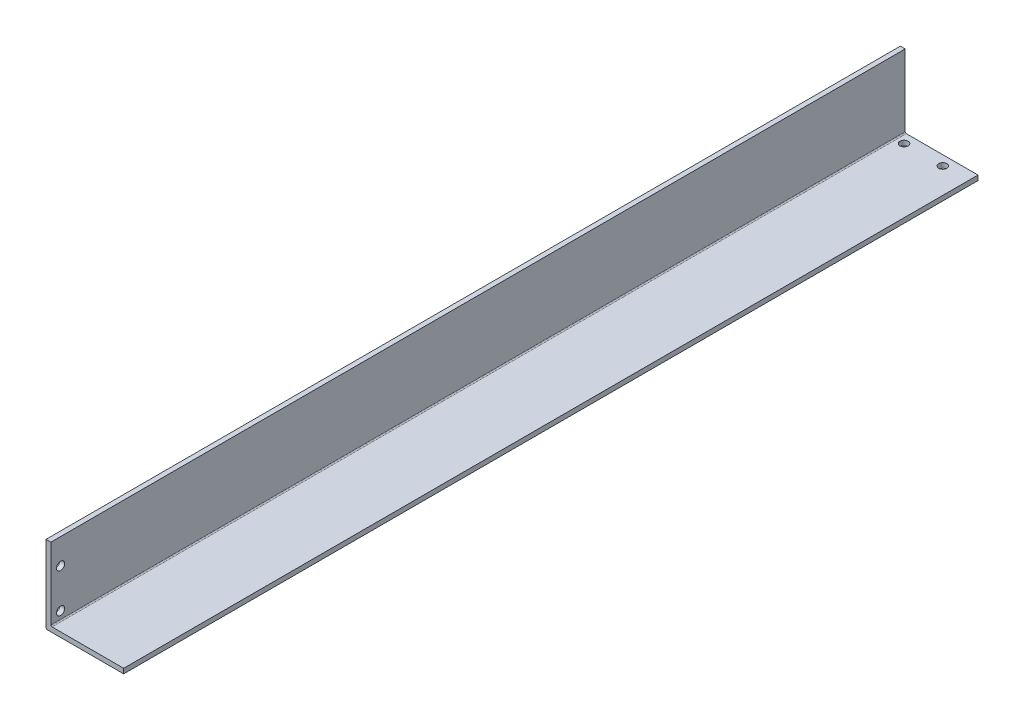
SolidWorks part; units mm, degrees
ref_plane "Front Plane" through (0, 0, 0) normal (0, 0, 1) x (1, 0, 0)
ref_plane "Top Plane" through (0, 0, 0) normal (0, 1, 0) x (1, 0, 0)
ref_plane "Right Plane" through (0, 0, 0) normal (1, 0, 0) x (0, 0, -1)
sketch "Sketch1" plane through (0, 0, 0) normal (0, 0, 1) x (1, 0, 0)
  line L0 (3.175, 50.8) -> (3.175, 3.937)
  line L1 (0.762, 0) -> (50.8, 0)
  line L2 (0, 0.762) -> (0, 50.8)
  line L3 (0, 50.8) -> (3.175, 50.8)
  line L4 (50.8, 0) -> (50.8, 3.175)
  line L5 (3.937, 3.175) -> (50.8, 3.175)
  arc A0 (0, 0.762) -> (0.762, 0) centre (0.762, 0.762) ccw
  arc A1 (3.175, 3.937) -> (3.937, 3.175) centre (3.937, 3.937) ccw
  point P10 (0, 0)
  dimension "D5" = 0.762
  dimension "D6" = 0.762
  dimension "D1" = 50.8
  dimension "D2" = 50.8
  dimension "D3" = 3.175
  dimension "D4" = 3.175
extrude "Boss-Extrude1" add sketch "Sketch1" along normal blind 558.8
sketch "Sketch2" plane through (0, 3.175, 0) normal (0, 1, 0) x (1, 0, 0)
  line L0 (34.163, -6.35) -> (34.163, 0)
  line L1 (50.8, 0) -> (3.937, 0) construction
  line L2 (8.763, -6.35) -> (34.163, -6.35)
  line L3 (34.163, -6.35) -> (50.8, -6.35)
  line L4 (50.8, -558.8) -> (50.8, 0) construction
  circle A0 centre (34.163, -6.35) radius 2.667
  circle A1 centre (8.763, -6.35) radius 2.667
  dimension "D2" = 5.334
  dimension "D1" = 6.35
  dimension "D3" = 16.637
  dimension "D4" = 25.4
extrude "Cut-Extrude1" cut sketch "Sketch2" against normal through all contours A0 | A1
sketch "Sketch3" plane through (3.175, 0, 0) normal (1, 0, 0) x (0, 0, -1)
  line L0 (-552.45, 8.763) -> (-552.45, 34.163)
  line L1 (-552.45, 34.163) -> (-558.8, 34.163)
  line L2 (-558.8, 3.937) -> (-558.8, 50.8) construction
  line L3 (-552.45, 34.163) -> (-552.45, 50.8)
  line L4 (-558.8, 50.8) -> (0, 50.8) construction
  circle A0 centre (-552.45, 34.163) radius 2.667
  circle A1 centre (-552.45, 8.763) radius 2.667
  dimension "D1" = 5.334
  dimension "D2" = 5.334
  dimension "D3" = 16.637
  dimension "D4" = 25.4
  dimension "D5" = 6.35
extrude "Cut-Extrude2" cut sketch "Sketch3" against normal through all contours A0 | A1
